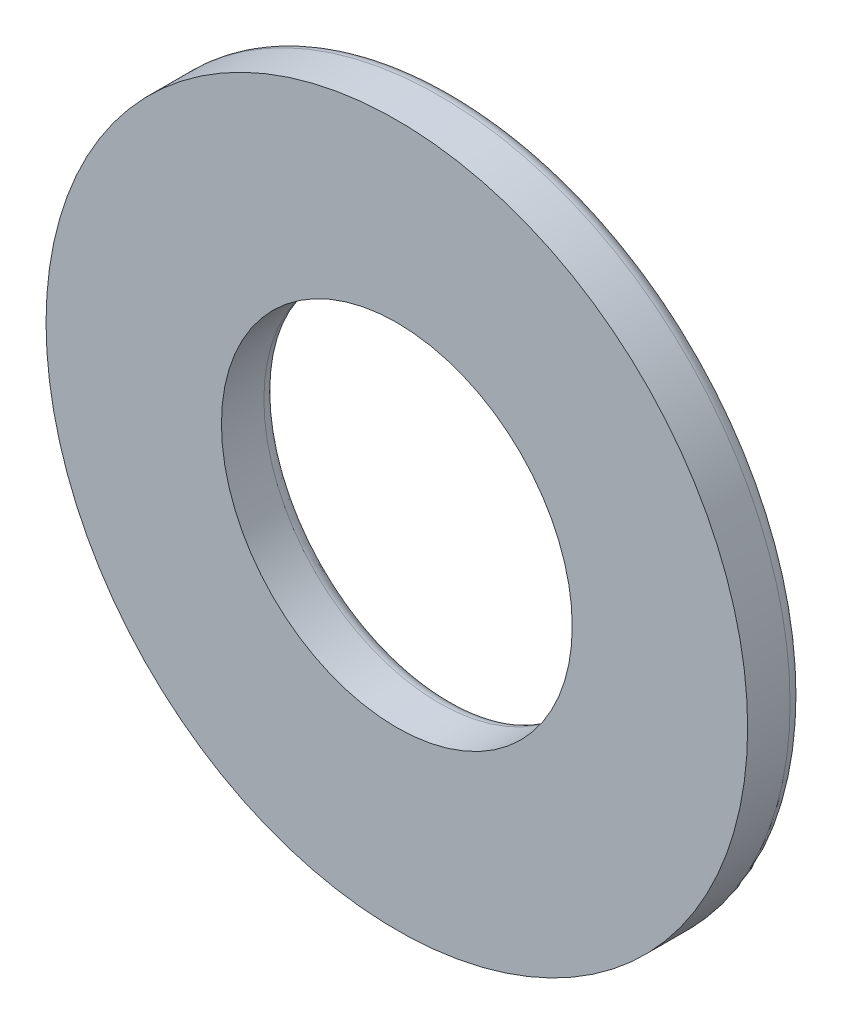
SolidWorks part; units mm, degrees
ref_plane "Front Plane" through (0, 0, 0) normal (0, 0, 1) x (1, 0, 0)
ref_plane "Top Plane" through (0, 0, 0) normal (0, 1, 0) x (1, 0, 0)
ref_plane "Right Plane" through (0, 0, 0) normal (1, 0, 0) x (0, 0, -1)
sketch "Sketch1" plane through (0, 0, 0) normal (0, 0, 1) x (1, 0, 0)
  line L0 (-10.3124, 0) -> (10.3124, 0) construction
  line L1 (0, 10.3124) -> (0, -10.3124) construction
  circle A0 centre (0, 0) radius 10.3124 construction
  circle A1 centre (0, 0) radius 5.1562 construction
  point P4 (0, 0)
  point P8 (0, -5.1562)
  point P9 (5.1562, 0)
  point P10 (0, 5.1562)
  point P11 (-5.1562, 0)
  dimension "OD" = 20.6248
  dimension "ID" = 10.3124
sketch "Sketch2" plane through (0, 0, 0) normal (1, 0, 0) x (0, 0, -1)
  line L0 (0.8319, 0) -> (-0.8319, 0) construction
  line L1 (0.8318, 10.3124) -> (-0.8319, 10.3124) construction
  line L2 (0.8318, 10.3124) -> (0.8318, -10.3124) construction
  line L3 (0.8318, -10.3124) -> (-0.8319, -10.3124) construction
  line L4 (-0.8319, 10.3124) -> (-0.8319, -10.3124) construction
  line L5 (-0.8319, 5.1562) -> (0.8318, 5.1562) construction
  line L6 (-0.8319, -5.1562) -> (0.8318, -5.1562) construction
  line L7 (-1.016, 0) -> (1.016, 0) construction
  line L8 (0, 10.3124) -> (0, -10.3124) construction
  point P6 (0, 0)
  point P17 (0, 0)
  point P18 (-0.6477, 0)
  point P21 (0.6477, 0)
  dimension "Thickness" = 1.6637
  dimension "Max Thickness Range" = 2.032
  dimension "Min Thickness Range" = 1.2954
sketch "Sketch3" plane through (0, 0, 0) normal (0, 0, 1) x (1, 0, 0)
  line L0 (-10.3124, 0) -> (10.3124, 0) construction
  circle A0 centre (0, 0) radius 10.3124
  circle A1 centre (0, 0) radius 5.1562
  circle A2 centre (0, 0) radius 10.3124 construction
  circle A3 centre (0, 0) radius 5.1562 construction
extrude "Boss-Extrude1" add sketch "Sketch3" along normal up to vertex (0.8318 mm away) and the other way up to vertex (0.8318 mm away) up to point (0, 0, 0.8319) other way up to point (0, 0, -0.8319)
fillet "Fillet1" radius 0.4159 2 edges at (10.3124, 0, -0.8319) (5.1562, 0, -0.8319)
equation "\"D1@Fillet1\"=\"Thickness@Sketch2\"*.25"
